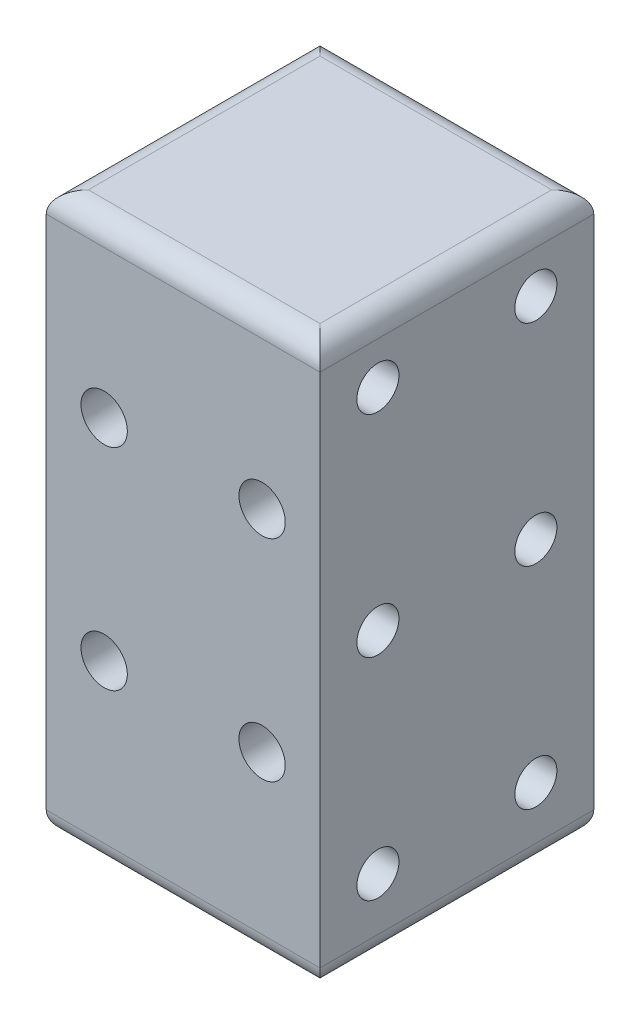
SolidWorks part; units mm, degrees
ref_plane "前视基准面" through (0, 0, 0) normal (0, 0, 1) x (1, 0, 0)
ref_plane "上视基准面" through (0, 0, 0) normal (0, 1, 0) x (1, 0, 0)
ref_plane "右视基准面" through (0, 0, 0) normal (1, 0, 0) x (0, 0, -1)
other "Configuration Table"
sketch "草图1" plane through (0, 0, 0) normal (0, 1, 0) x (1, 0, 0)
  line L1 (-13, 13) -> (13, 13)
  line L2 (-13, 13) -> (-13, -13)
  line L3 (-13, -13) -> (13, -13)
  line L4 (13, 13) -> (13, -13)
  line L5 (-13, 13) -> (13, -13) construction
  line L6 (-13, -13) -> (13, 13) construction
  point P0 (0, 0)
  dimension "D1" = 26
  dimension "D2" = 26
extrude "凸台-拉伸1" add sketch "草图1" along normal blind 53
fillet "圆角2" radius 2 8 edges at (0, 53, 13) (-13, 53, 0) (0, 53, -13) (13, 53, 0) (0, 0, -13) (-13, 0, 0) (0, 0, 13) (13, 0, 0)
sketch "草图2" plane through (0, 0, 13) normal (0, 0, 1) x (1, 0, 0)
  line L4 (13, 2) -> (13, 51)
  line L5 (13, 51) -> (-13, 51)
  line L6 (-13, 51) -> (-13, 2)
  line L7 (-13, 2) -> (13, 2)
  line L8 (13, 2) -> (13, 51)
  line L9 (13, 51) -> (-13, 51)
  line L10 (-13, 51) -> (-13, 2)
  line L11 (-13, 2) -> (13, 2)
  circle A0 centre (7.5, 17) radius 1.55 construction
  circle A1 centre (7.5, 37) radius 1.55 construction
  circle A2 centre (-7.5, 17) radius 1.55 construction
  circle A3 centre (-7.5, 37) radius 1.55 construction
  circle A4 centre (7.5, 17) radius 1.55
  circle A5 centre (7.5, 37) radius 1.55
  circle A6 centre (-7.5, 17) radius 1.55
  circle A7 centre (-7.5, 37) radius 1.55
  dimension "D1" = 0
extrude "切除-拉伸1" cut sketch "草图2" against normal up to next contours A7 | A5 | A6 | A4
sketch "草图3" plane through (-13, 0, 0) normal (-1, 0, 0) x (0, 0, 1)
  line L4 (13, 2) -> (13, 51)
  line L5 (13, 51) -> (-13, 51)
  line L6 (-13, 51) -> (-13, 2)
  line L7 (-13, 2) -> (13, 2)
  line L8 (13, 2) -> (13, 51)
  line L9 (13, 51) -> (-13, 51)
  line L10 (-13, 51) -> (-13, 2)
  line L11 (-13, 2) -> (13, 2)
  circle A0 centre (7.5, 7) radius 2 construction
  circle A1 centre (7.5, 27) radius 2 construction
  circle A2 centre (7.5, 47) radius 2 construction
  circle A3 centre (-7.5, 7) radius 2 construction
  circle A4 centre (-7.5, 27) radius 2 construction
  circle A5 centre (-7.5, 47) radius 2 construction
  circle A6 centre (7.5, 7) radius 2
  circle A7 centre (7.5, 27) radius 2
  circle A8 centre (7.5, 47) radius 2
  circle A9 centre (-7.5, 7) radius 2
  circle A10 centre (-7.5, 27) radius 2
  circle A11 centre (-7.5, 47) radius 2
  dimension "D1" = 0
extrude "切除-拉伸2" cut sketch "草图3" against normal up to next contours A11 | A8 | A10 | A7 | A9 | A6
sketch "草图4" plane through (0, 0, -13) normal (0, 0, -1) x (-1, 0, 0)
  circle A0 centre (-7.5, 37) radius 2.2
  circle A1 centre (7.5, 37) radius 2.2
  circle A2 centre (7.5, 17) radius 2.2
  circle A3 centre (-7.5, 17) radius 2.2
  dimension "D1" = 4.4
  dimension "D2" = 4.4
  dimension "D3" = 4.4
  dimension "D4" = 4.4
extrude "切除-拉伸3" cut sketch "草图4" against normal up to next
